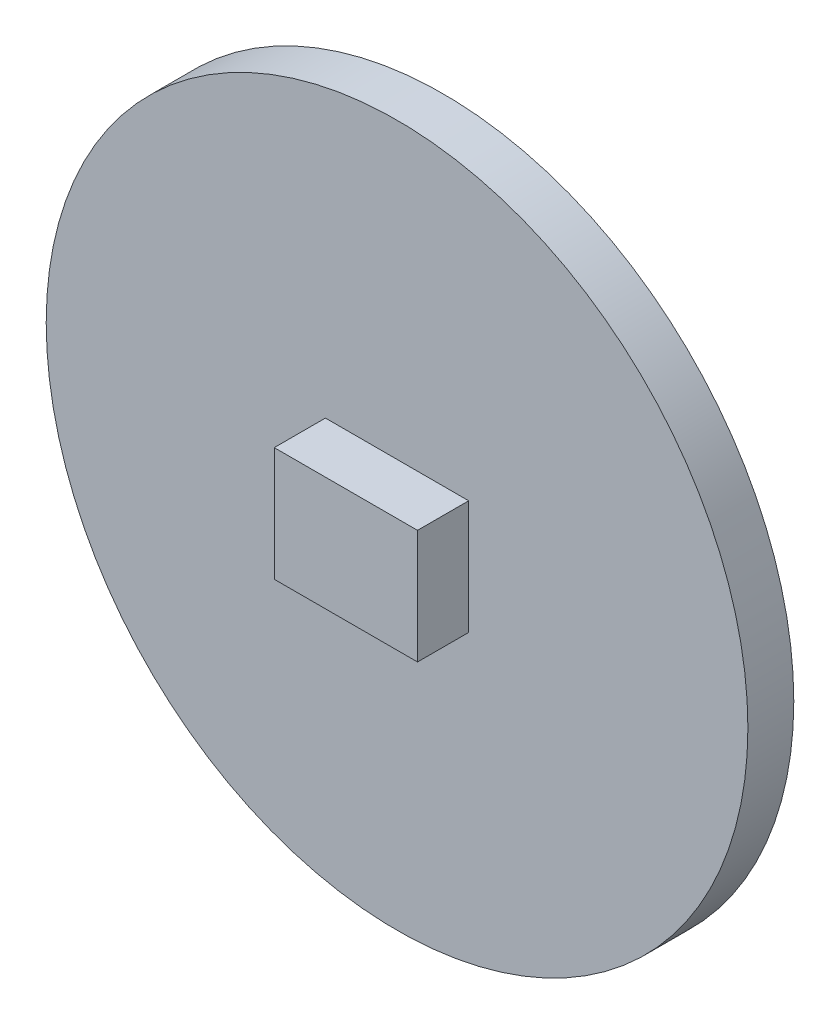
SolidWorks part; units mm, degrees
ref_plane "Front Plane" through (0, 0, 0) normal (0, 0, 1) x (1, 0, 0)
ref_plane "Top Plane" through (0, 0, 0) normal (0, 1, 0) x (1, 0, 0)
ref_plane "Right Plane" through (0, 0, 0) normal (1, 0, 0) x (0, 0, -1)
sketch "Sketch1" plane through (0, 0, 0) normal (0, 0, 1) x (1, 0, 0)
  circle A0 centre (0, 0) radius 12
  dimension "D1" = 24
extrude "Boss-Extrude1" add sketch "Sketch1" along normal blind 1.57
sketch "Sketch2" plane through (0, 0, 1.57) normal (0, 0, 1) x (1, 0, 0)
  line L1 (2.45, -1.95) -> (-2.45, -1.95)
  line L2 (2.45, -1.95) -> (2.45, 1.95)
  line L3 (2.45, 1.95) -> (-2.45, 1.95)
  line L4 (-2.45, -1.95) -> (-2.45, 1.95)
  line L5 (2.45, -1.95) -> (-2.45, 1.95) construction
  line L6 (2.45, 1.95) -> (-2.45, -1.95) construction
  point P0 (0, 0)
  dimension "D1" = 4.9
  dimension "D2" = 3.9
extrude "Boss-Extrude2" add sketch "Sketch2" along normal blind 1.75
